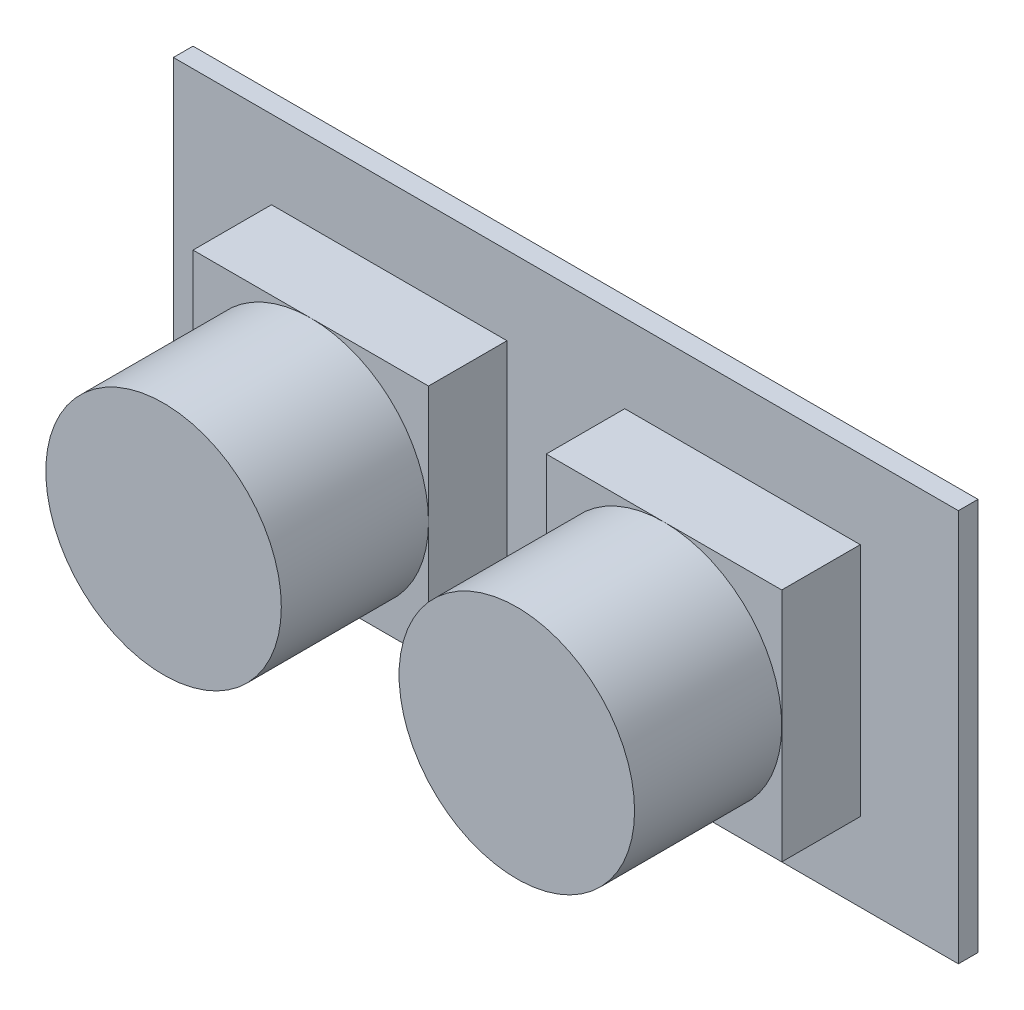
SolidWorks part; units mm, degrees
ref_plane "Plan de face" through (0, 0, 0) normal (0, 0, 1) x (1, 0, 0)
ref_plane "Plan de dessus" through (0, 0, 0) normal (0, 1, 0) x (1, 0, 0)
ref_plane "Plan de droite" through (0, 0, 0) normal (1, 0, 0) x (0, 0, -1)
sketch "Esquisse 1" plane through (0, 0, 0) normal (0, 0, 1) x (1, 0, 0)
  line L1 (0, 0) -> (4, 0)
  line L2 (0, 0) -> (0, 2)
  line L3 (0, 2) -> (4, 2)
  line L4 (4, 0) -> (4, 2)
  dimension "D1" = 2
  dimension "D2" = 4
sketch "Esquisse 2" plane through (0, 0, 0) normal (0, 0, 1) x (1, 0, 0)
  line L0 (0, 0) -> (0, 2) construction
  line L5 (1.7, 0.4) -> (0.5, 0.4)
  line L6 (1.7, 0.4) -> (1.7, 1.6)
  line L7 (1.7, 1.6) -> (0.5, 1.6)
  line L8 (0.5, 0.4) -> (0.5, 1.6)
  line L14 (0.5, 1.6) -> (0.5, 2) construction
  line L15 (0, 2) -> (4, 2) construction
  line L16 (0.5, 0.4) -> (1.7, 1.6) construction
  line L17 (0.5, 1.6) -> (1.7, 0.4) construction
  line L18 (0.5, 0.4) -> (0.5, 0) construction
  line L19 (0, 0) -> (4, 0) construction
  line L20 (3.5, 0.4) -> (2.3, 0.4)
  line L21 (3.5, 0.4) -> (3.5, 1.6)
  line L22 (3.5, 1.6) -> (2.3, 1.6)
  line L23 (2.3, 0.4) -> (2.3, 1.6)
  line L24 (2.3, 0.4) -> (3.5, 1.6) construction
  line L25 (2.3, 1.6) -> (3.5, 0.4) construction
  line L26 (4, 0) -> (4, 2) construction
  dimension "D3" = 1.2
  dimension "D4" = 1.2
  dimension "D1" = 0.5
  dimension "D2" = 1.2
  dimension "D5" = 1.2
  dimension "D6" = 0.5
sketch "Esquisse 3" plane through (0, 0, 0) normal (0, 0, 1) x (1, 0, 0)
  line L0 (2.3, 0.4) -> (3.5, 1.6) construction
  line L13 (0.5, 1.6) -> (1.7, 0.4) construction
  circle A2 centre (1.1, 1) radius 0.6
  circle A4 centre (2.9, 1) radius 0.6
  dimension "D9" = 1.2
  dimension "D1" = 1.2
extrude "Boss.-Extru.2" add sketch "Esquisse 1" along normal blind 0.1
extrude "Boss.-Extru.3" add sketch "Esquisse 2" along normal blind 0.5
extrude "Boss.-Extru.4" add sketch "Esquisse 3" along normal blind 1.25
